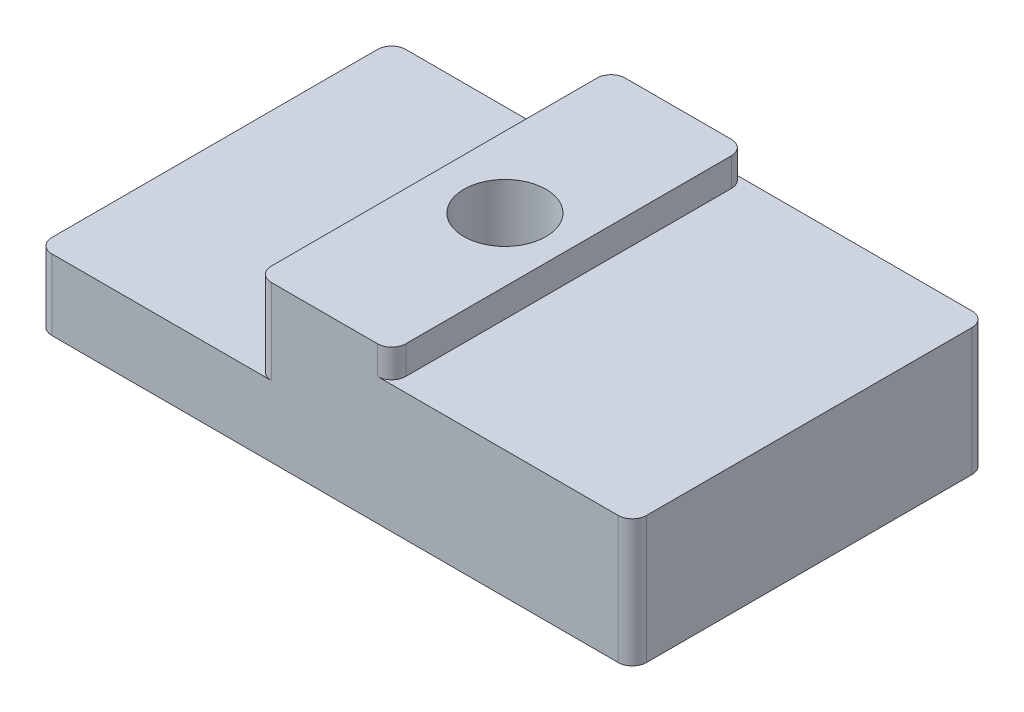
SolidWorks part; units mm, degrees
ref_plane "Front Plane" through (0, 0, 0) normal (0, 0, 1) x (1, 0, 0)
ref_plane "Top Plane" through (0, 0, 0) normal (0, 1, 0) x (1, 0, 0)
ref_plane "Right Plane" through (0, 0, 0) normal (1, 0, 0) x (0, 0, -1)
sketch "Sketch1" plane through (0, 0, 0) normal (0, 1, 0) x (1, 0, 0)
  line L1 (0, 0) -> (45, 0)
  line L2 (0, 0) -> (0, 25)
  line L3 (0, 25) -> (45, 25)
  line L4 (45, 0) -> (45, 25)
  dimension "D1" = 45
  dimension "D2" = 25
extrude "Boss-Extrude1" add sketch "Sketch1" along normal blind 5 contours L1 L4 L3 L2
sketch "Sketch5" plane through (0, 5, 0) normal (0, 1, 0) x (1, 0, 0)
  line L0 (0, 25) -> (45, 25) construction
  line L1 (18.5, 25) -> (45, 25)
  line L2 (18.5, 25) -> (18.5, 0)
  line L3 (18.5, 0) -> (45, 0)
  line L4 (45, 25) -> (45, 0)
  line L5 (45, 0) -> (45, 25) construction
  line L6 (0, 0) -> (45, 0) construction
  dimension "D1" = 26.5
extrude "Boss-Extrude3" add sketch "Sketch5" along normal blind 4
sketch "Sketch11" plane through (0, 9, 0) normal (0, 1, 0) x (1, 0, 0)
  line L0 (18.5, 25) -> (18.5, 0) construction
  line L1 (18.5, 25) -> (28, 25)
  line L2 (18.5, 25) -> (18.5, 0)
  line L3 (18.5, 0) -> (28, 0)
  line L4 (28, 25) -> (28, 0)
  line L5 (45, 25) -> (18.5, 25) construction
  line L6 (18.5, 0) -> (45, 0) construction
  dimension "D1" = 9.5
extrude "Boss-Extrude5" add sketch "Sketch11" along normal blind 2
sketch "Sketch12" plane through (0, 5, 0) normal (0, 1, 0) x (1, 0, 0)
  line L0 (0, 25) -> (18.5, 25) construction
  line L1 (0, 25) -> (3, 25)
  line L2 (0, 25) -> (0, 0)
  line L3 (0, 0) -> (3, 0)
  line L4 (3, 25) -> (3, 0)
  line L5 (0, 0) -> (0, 25) construction
  line L6 (0, 0) -> (18.5, 0) construction
  dimension "D1" = 3
extrude "Cut-Extrude2" cut sketch "Sketch12" against normal through all
sketch "Sketch13" plane through (0, 0, 0) normal (0, -1, 0) x (-1, 0, 0)
  line L0 (-23.5, 0) -> (-23.5, 25) construction
  line L1 (-3, 0) -> (-45, 0) construction
  line L2 (-3, 25) -> (-45, 25) construction
  line L3 (-45, 0) -> (-45, 25) construction
  point P8 (-23.5, 12.5)
  dimension "D1" = 21.5
hole_wizard "M5 Clearance Hole1" positions "Sketch14" profile "Sketch15" hole size "M5" standard "ISO" end condition through all
sketch "Sketch14" plane through (0, 0, 0) normal (0, -1, 0) x (-1, 0, 0)
  point P0 (-23.5, 12.5)
sketch "Sketch15" plane through (23.5, 0, -12.5) normal (1, 0, 0) x (0, 0, -1)
  line L0 (0, 0) -> (0, 11)
  line L1 (0, 11) -> (2.9, 11)
  line L2 (2.9, 11) -> (2.9, 0)
  line L5 (2.9, 0) -> (0, 0)
  line L11 (0, -6.35) -> (0, 107.95) construction
  dimension "Thru Hole Dia." = 5.8
  dimension "Thru Hole Depth" = 11
fillet "Fillet2" radius 1 8 edges at (28, 10, 0) (18.5, 8, 0) (18.5, 8, -25) (28, 10, -25) (3, 2.5, -25) (3, 2.5, 0) (45, 4.5, 0) (45, 4.5, -25)
